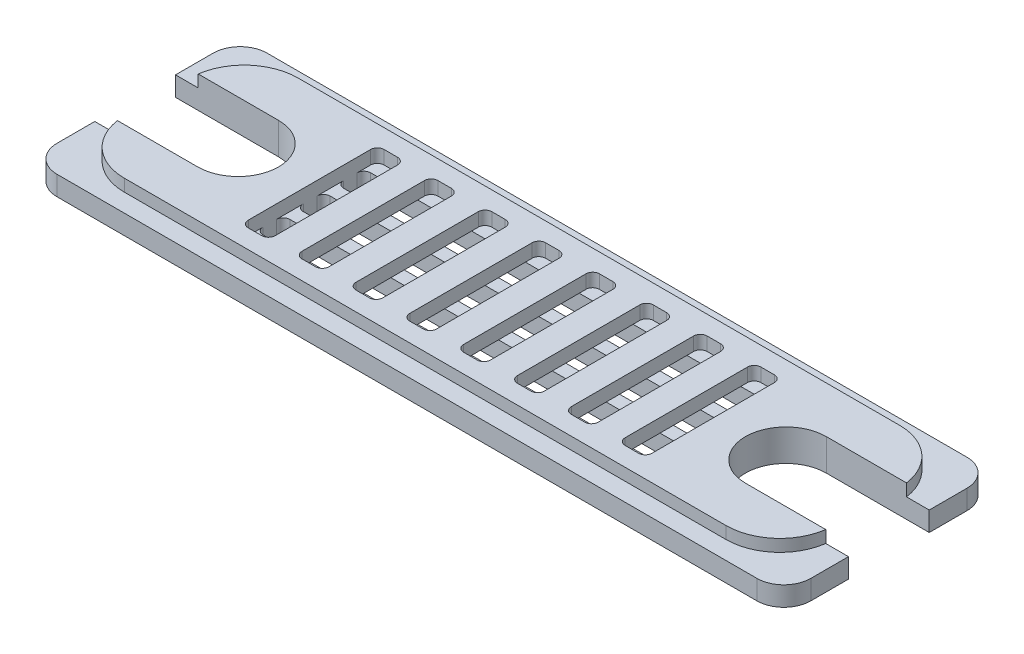
SolidWorks part; units mm, degrees
ref_plane "Front Plane" through (0, 0, 0) normal (0, 0, 1) x (1, 0, 0)
ref_plane "Top Plane" through (0, 0, 0) normal (0, 1, 0) x (1, 0, 0)
ref_plane "Right Plane" through (0, 0, 0) normal (1, 0, 0) x (0, 0, -1)
sketch "Sketch1" plane through (0, 0, 0) normal (0, 1, 0) x (1, 0, 0)
  line L1 (-26, -7.8) -> (26, -7.8)
  line L2 (-28, -5.8) -> (-28, 5.8)
  line L3 (-26, 7.8) -> (26, 7.8)
  line L4 (28, -5.8) -> (28, 5.8)
  line L5 (-28, -7.8) -> (28, 7.8) construction
  line L6 (-28, 7.8) -> (28, -7.8) construction
  arc A0 (26, 7.8) -> (28, 5.8) centre (26, 5.8) cw
  arc A1 (26, -7.8) -> (28, -5.8) centre (26, -5.8) ccw
  arc A2 (-26, -7.8) -> (-28, -5.8) centre (-26, -5.8) cw
  arc A3 (-28, 5.8) -> (-26, 7.8) centre (-26, 5.8) cw
  point P0 (0, 0)
  dimension "D3" = 2
  dimension "D1" = 56
  dimension "D2" = 15.6
extrude "Boss-Extrude1" add sketch "Sketch1" along normal blind 1.45
sketch "Sketch2" plane through (0, 1.45, 0) normal (0, 1, 0) x (1, 0, 0)
  line L1 (-22.35, -6.45) -> (22.35, -6.45)
  line L2 (-26.35, -2.45) -> (-26.35, 2.45)
  line L3 (-22.35, 6.45) -> (22.35, 6.45)
  line L4 (26.35, -2.45) -> (26.35, 2.45)
  line L5 (-26.35, -6.45) -> (26.35, 6.45) construction
  line L6 (-26.35, 6.45) -> (26.35, -6.45) construction
  arc A0 (22.35, -6.45) -> (26.35, -2.45) centre (22.35, -2.45) ccw
  arc A1 (22.35, 6.45) -> (26.35, 2.45) centre (22.35, 2.45) cw
  arc A2 (-22.35, -6.45) -> (-26.35, -2.45) centre (-22.35, -2.45) cw
  arc A3 (-26.35, 2.45) -> (-22.35, 6.45) centre (-22.35, 2.45) cw
  point P0 (0, 0)
  dimension "D3" = 4
  dimension "D1" = 52.7
  dimension "D2" = 12.9
extrude "Boss-Extrude2" add sketch "Sketch2" along normal blind 0.9
sketch "Sketch3" plane through (0, 2.35, 0) normal (0, 1, 0) x (1, 0, 0)
  line L0 (35.4623, 0) -> (-35.0934, 0) construction
  line L1 (-14.55, 5.0461) -> (-13.55, 5.0461)
  line L2 (-15.05, 4.5461) -> (-15.05, -4.5461)
  line L3 (-14.55, -5.0461) -> (-13.55, -5.0461)
  line L4 (-13.05, 4.5461) -> (-13.05, -4.5461)
  line L5 (-15.05, 5.0461) -> (-13.05, -5.0461) construction
  line L6 (-15.05, -5.0461) -> (-13.05, 5.0461) construction
  line L7 (22.35, 6.45) -> (-22.35, 6.45) construction
  line L8 (-26.35, 2.45) -> (-26.35, -2.45) construction
  line L9 (-10.55, 5.0461) -> (-9.55, 5.0461)
  line L10 (-11.05, 4.5461) -> (-11.05, -4.5461)
  line L11 (-10.55, -5.0461) -> (-9.55, -5.0461)
  line L12 (-9.05, 4.5461) -> (-9.05, -4.5461)
  line L13 (-11.05, 5.0461) -> (-9.05, -5.0461) construction
  line L14 (-11.05, -5.0461) -> (-9.05, 5.0461) construction
  line L15 (-6.55, 5.0461) -> (-5.55, 5.0461)
  line L16 (-7.05, 4.5461) -> (-7.05, -4.5461)
  line L17 (-6.55, -5.0461) -> (-5.55, -5.0461)
  line L18 (-5.05, 4.5461) -> (-5.05, -4.5461)
  line L19 (-7.05, 5.0461) -> (-5.05, -5.0461) construction
  line L20 (-7.05, -5.0461) -> (-5.05, 5.0461) construction
  line L21 (-2.55, 5.0461) -> (-1.55, 5.0461)
  line L22 (-3.05, 4.5461) -> (-3.05, -4.5461)
  line L23 (-2.55, -5.0461) -> (-1.55, -5.0461)
  line L24 (-1.05, 4.5461) -> (-1.05, -4.5461)
  line L25 (-3.05, 5.0461) -> (-1.05, -5.0461) construction
  line L26 (-3.05, -5.0461) -> (-1.05, 5.0461) construction
  line L27 (1.45, 5.0461) -> (2.45, 5.0461)
  line L28 (0.95, 4.5461) -> (0.95, -4.5461)
  line L29 (1.45, -5.0461) -> (2.45, -5.0461)
  line L30 (2.95, 4.5461) -> (2.95, -4.5461)
  line L31 (0.95, 5.0461) -> (2.95, -5.0461) construction
  line L32 (0.95, -5.0461) -> (2.95, 5.0461) construction
  line L33 (5.45, 5.0461) -> (6.45, 5.0461)
  line L34 (4.95, 4.5461) -> (4.95, -4.5461)
  line L35 (5.45, -5.0461) -> (6.45, -5.0461)
  line L36 (6.95, 4.5461) -> (6.95, -4.5461)
  line L37 (4.95, 5.0461) -> (6.95, -5.0461) construction
  line L38 (4.95, -5.0461) -> (6.95, 5.0461) construction
  line L39 (9.45, 5.0461) -> (10.45, 5.0461)
  line L40 (8.95, 4.5461) -> (8.95, -4.5461)
  line L41 (9.45, -5.0461) -> (10.45, -5.0461)
  line L42 (10.95, 4.5461) -> (10.95, -4.5461)
  line L43 (8.95, 5.0461) -> (10.95, -5.0461) construction
  line L44 (8.95, -5.0461) -> (10.95, 5.0461) construction
  line L45 (13.45, 5.0461) -> (14.45, 5.0461)
  line L46 (12.95, 4.5461) -> (12.95, -4.5461)
  line L47 (13.45, -5.0461) -> (14.45, -5.0461)
  line L48 (14.95, 4.5461) -> (14.95, -4.5461)
  line L49 (12.95, 5.0461) -> (14.95, -5.0461) construction
  line L50 (12.95, -5.0461) -> (14.95, 5.0461) construction
  arc A0 (-15.05, -4.5461) -> (-14.55, -5.0461) centre (-14.55, -4.5461) ccw
  arc A1 (-13.55, -5.0461) -> (-13.05, -4.5461) centre (-13.55, -4.5461) ccw
  arc A2 (-13.55, 5.0461) -> (-13.05, 4.5461) centre (-13.55, 4.5461) cw
  arc A3 (-14.55, 5.0461) -> (-15.05, 4.5461) centre (-14.55, 4.5461) ccw
  arc A4 (-11.05, -4.5461) -> (-10.55, -5.0461) centre (-10.55, -4.5461) ccw
  arc A5 (-9.55, -5.0461) -> (-9.05, -4.5461) centre (-9.55, -4.5461) ccw
  arc A6 (-9.55, 5.0461) -> (-9.05, 4.5461) centre (-9.55, 4.5461) cw
  arc A7 (-10.55, 5.0461) -> (-11.05, 4.5461) centre (-10.55, 4.5461) ccw
  arc A8 (-7.05, -4.5461) -> (-6.55, -5.0461) centre (-6.55, -4.5461) ccw
  arc A9 (-5.55, -5.0461) -> (-5.05, -4.5461) centre (-5.55, -4.5461) ccw
  arc A10 (-5.55, 5.0461) -> (-5.05, 4.5461) centre (-5.55, 4.5461) cw
  arc A11 (-6.55, 5.0461) -> (-7.05, 4.5461) centre (-6.55, 4.5461) ccw
  arc A12 (-3.05, -4.5461) -> (-2.55, -5.0461) centre (-2.55, -4.5461) ccw
  arc A13 (-1.55, -5.0461) -> (-1.05, -4.5461) centre (-1.55, -4.5461) ccw
  arc A14 (-1.55, 5.0461) -> (-1.05, 4.5461) centre (-1.55, 4.5461) cw
  arc A15 (-2.55, 5.0461) -> (-3.05, 4.5461) centre (-2.55, 4.5461) ccw
  arc A16 (0.95, -4.5461) -> (1.45, -5.0461) centre (1.45, -4.5461) ccw
  arc A17 (2.45, -5.0461) -> (2.95, -4.5461) centre (2.45, -4.5461) ccw
  arc A18 (2.45, 5.0461) -> (2.95, 4.5461) centre (2.45, 4.5461) cw
  arc A19 (1.45, 5.0461) -> (0.95, 4.5461) centre (1.45, 4.5461) ccw
  arc A20 (4.95, -4.5461) -> (5.45, -5.0461) centre (5.45, -4.5461) ccw
  arc A21 (6.45, -5.0461) -> (6.95, -4.5461) centre (6.45, -4.5461) ccw
  arc A22 (6.45, 5.0461) -> (6.95, 4.5461) centre (6.45, 4.5461) cw
  arc A23 (5.45, 5.0461) -> (4.95, 4.5461) centre (5.45, 4.5461) ccw
  arc A24 (8.95, -4.5461) -> (9.45, -5.0461) centre (9.45, -4.5461) ccw
  arc A25 (10.45, -5.0461) -> (10.95, -4.5461) centre (10.45, -4.5461) ccw
  arc A26 (10.45, 5.0461) -> (10.95, 4.5461) centre (10.45, 4.5461) cw
  arc A27 (9.45, 5.0461) -> (8.95, 4.5461) centre (9.45, 4.5461) ccw
  arc A28 (12.95, -4.5461) -> (13.45, -5.0461) centre (13.45, -4.5461) ccw
  arc A29 (14.45, -5.0461) -> (14.95, -4.5461) centre (14.45, -4.5461) ccw
  arc A30 (14.45, 5.0461) -> (14.95, 4.5461) centre (14.45, 4.5461) cw
  arc A31 (13.45, 5.0461) -> (12.95, 4.5461) centre (13.45, 4.5461) ccw
  point P0 (-14.05, 0)
  point P26 (-10.05, 0)
  point P43 (-6.05, 0)
  point P60 (-2.05, 0)
  point P77 (1.95, 0)
  point P94 (5.95, 0)
  point P111 (9.95, 0)
  point P128 (13.95, 0)
  dimension "D4" = 0.5
  dimension "D1" = 1.4039
  dimension "D2" = 11.3
  dimension "D3" = 2
  dimension "D5" = 8
extrude "Cut-Extrude1" cut sketch "Sketch3" against normal blind 1
sketch "Sketch4" plane through (0, 1.35, 0) normal (0, 1, 0) x (1, 0, 0)
  line L0 (-15.05, 4.5461) -> (-15.05, -4.5461) construction
  line L1 (-14.55, 4.0461) -> (14.45, 4.0461)
  line L2 (-15.05, 3.5461) -> (-15.05, 2.5461)
  line L3 (-14.55, 2.0461) -> (14.45, 2.0461)
  line L4 (14.95, 3.5461) -> (14.95, 2.5461)
  line L6 (-13.55, 5.0461) -> (-14.55, 5.0461) construction
  line L7 (-14.55, 1.0461) -> (14.45, 1.0461)
  line L8 (-15.05, 0.5461) -> (-15.05, -0.4539)
  line L9 (-14.55, -0.9539) -> (14.45, -0.9539)
  line L10 (14.95, 0.5461) -> (14.95, -0.4539)
  line L11 (-14.55, -1.9539) -> (14.45, -1.9539)
  line L12 (-15.05, -2.4539) -> (-15.05, -3.4539)
  line L13 (-14.55, -3.9539) -> (14.45, -3.9539)
  line L14 (14.95, -2.4539) -> (14.95, -3.4539)
  line L16 (-15.05, 4.5461) -> (-15.05, -4.5461) construction
  line L17 (14.95, -4.5461) -> (14.95, 4.5461) construction
  arc A0 (14.45, -3.9539) -> (14.95, -3.4539) centre (14.45, -3.4539) ccw
  arc A1 (14.45, -1.9539) -> (14.95, -2.4539) centre (14.45, -2.4539) cw
  arc A2 (14.45, -0.9539) -> (14.95, -0.4539) centre (14.45, -0.4539) ccw
  arc A3 (14.45, 1.0461) -> (14.95, 0.5461) centre (14.45, 0.5461) cw
  arc A4 (14.45, 2.0461) -> (14.95, 2.5461) centre (14.45, 2.5461) ccw
  arc A5 (14.45, 4.0461) -> (14.95, 3.5461) centre (14.45, 3.5461) cw
  arc A6 (-15.05, -3.4539) -> (-14.55, -3.9539) centre (-14.55, -3.4539) ccw
  arc A7 (-14.55, -1.9539) -> (-15.05, -2.4539) centre (-14.55, -2.4539) ccw
  arc A8 (-15.05, -0.4539) -> (-14.55, -0.9539) centre (-14.55, -0.4539) ccw
  arc A9 (-14.55, 1.0461) -> (-15.05, 0.5461) centre (-14.55, 0.5461) ccw
  arc A10 (-15.05, 2.5461) -> (-14.55, 2.0461) centre (-14.55, 2.5461) ccw
  arc A11 (-14.55, 4.0461) -> (-15.05, 3.5461) centre (-14.55, 3.5461) ccw
  point P28 (14.95, 2.0461)
  point P41 (-15.05, 2.0461)
  point P44 (-15.05, 4.0461)
  dimension "D4" = 0.5
  dimension "D1" = 1
  dimension "D2" = 2
  dimension "D3" = 3
extrude "Cut-Extrude2" cut sketch "Sketch4" against normal up to next
sketch "Sketch5" plane through (0, 2.35, 0) normal (0, 1, 0) x (1, 0, 0)
  line L0 (31.4297, 0) -> (-32.1656, 0) construction
  line L1 (-26.35, 2.45) -> (-26.35, -2.45) construction
  line L2 (26.35, -2.45) -> (26.35, 2.45) construction
  line L3 (-20.35, 3) -> (-28, 3)
  line L4 (-20.35, -3) -> (-28, -3)
  line L6 (20.35, -3) -> (28, -3)
  line L7 (20.35, 3) -> (28, 3)
  line L9 (-28, 5.8) -> (-28, -5.8) construction
  line L10 (-28, 3) -> (-28, -3)
  line L11 (28, -5.8) -> (28, 5.8) construction
  line L12 (28, -3) -> (28, 3)
  arc A0 (-20.35, -3) -> (-20.35, 3) centre (-20.35, 0) ccw
  arc A1 (20.35, 3) -> (20.35, -3) centre (20.35, 0) ccw
  dimension "D1" = 6
  dimension "D2" = 6
  dimension "D3" = 6
extrude "Cut-Extrude3" cut sketch "Sketch5" against normal through all
